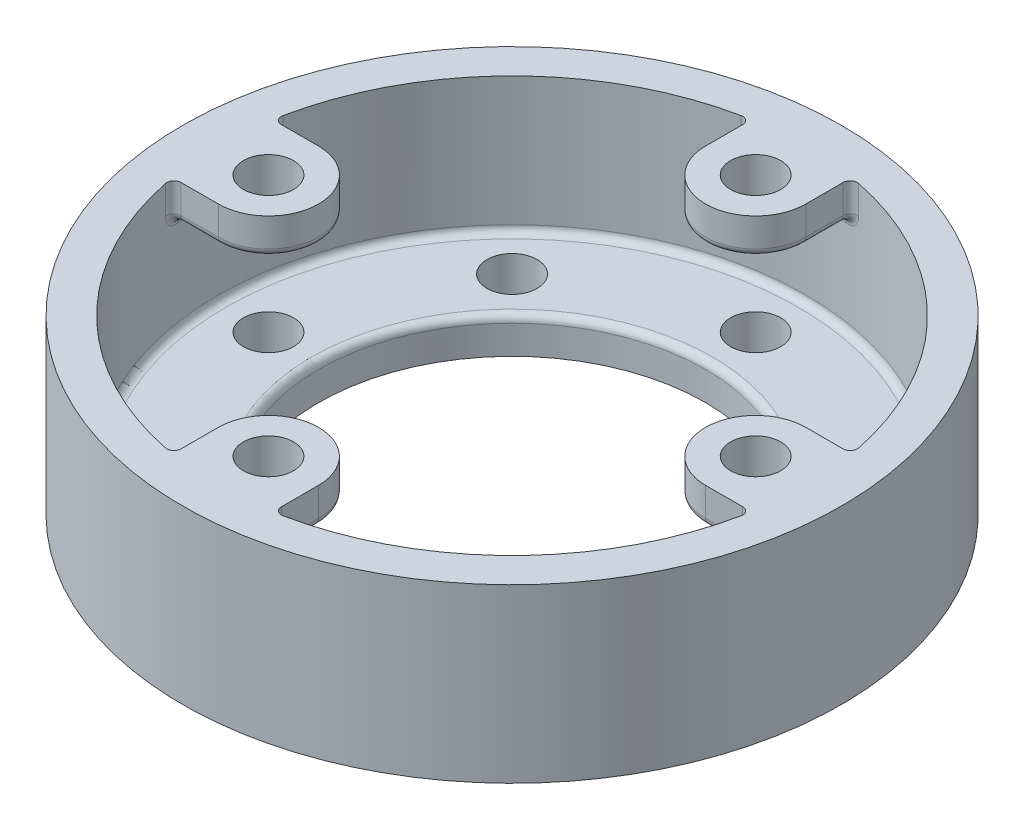
SolidWorks part; units mm, degrees
ref_plane "前基準面" through (0, 0, 0) normal (0, 0, 1) x (1, 0, 0)
ref_plane "上基準面" through (0, 0, 0) normal (0, 1, 0) x (1, 0, 0)
ref_plane "右基準面" through (0, 0, 0) normal (1, 0, 0) x (0, 0, -1)
sketch "草圖1" plane through (0, 0, 0) normal (0, 0, 1) x (1, 0, 0)
  line L0 (0, 0) -> (0, 67.9122) construction
  line L1 (27, 0) -> (27, 5)
  line L2 (27, 5) -> (41, 5)
  line L3 (41, 5) -> (41, 24)
  line L4 (41, 24) -> (46, 24)
  line L5 (46, 24) -> (46, 0)
  line L6 (46, 0) -> (27, 0)
  dimension "D1" = 54
  dimension "D2" = 82
  dimension "D3" = 92
  dimension "D4" = 5
  dimension "D5" = 24
revolve "旋轉1" add sketch "草圖1" angle 360 about L0
sketch "草圖2" plane through (0, 24, 0) normal (0, 1, 0) x (1, 0, 0)
  line L0 (-7, 40.398) -> (-7, 34)
  line L1 (7, 34) -> (7, 40.398)
  circle A0 centre (0, 0) radius 34 construction
  circle A1 centre (0, 0) radius 41 construction
  arc A2 (-7, 34) -> (7, 34) centre (0, 34) ccw
  arc A3 (7, 40.398) -> (-7, 40.398) centre (0, 0) ccw
  circle A4 centre (0, 34) radius 3.5
  dimension "D1" = 68
  dimension "D2" = 7
  dimension "D3" = 7
extrude "伸長1" add sketch "草圖2" against normal blind 5
sketch "草圖3" plane through (0, 5, 0) normal (0, 1, 0) x (1, 0, 0)
  circle A0 centre (0, 34) radius 3.5 construction
  circle A1 centre (0, 34) radius 3.5
extrude "伸長2" cut sketch "草圖3" against normal through all
fillet "圓角1" radius 1 6 edges at (0, 19, -41) (-7, 19, -37.199) (7, 19, -37.199) (0, 19, -27) (-7, 21.5, -40.398) (7, 21.5, -40.398)
fillet "圓角2" radius 1 2 edges at (0, 5, -27) (0, 5, -41)
pattern_circular "環狀複製排列1" count 4 over 360 about axis through (0, 24, 0) along (0, -1, 0) of "伸長1", "圓角1"
pattern_circular "環狀複製排列2" count 8 over 360 about axis through (0, 0, 0) along (0, 1, 0) of "伸長2"
